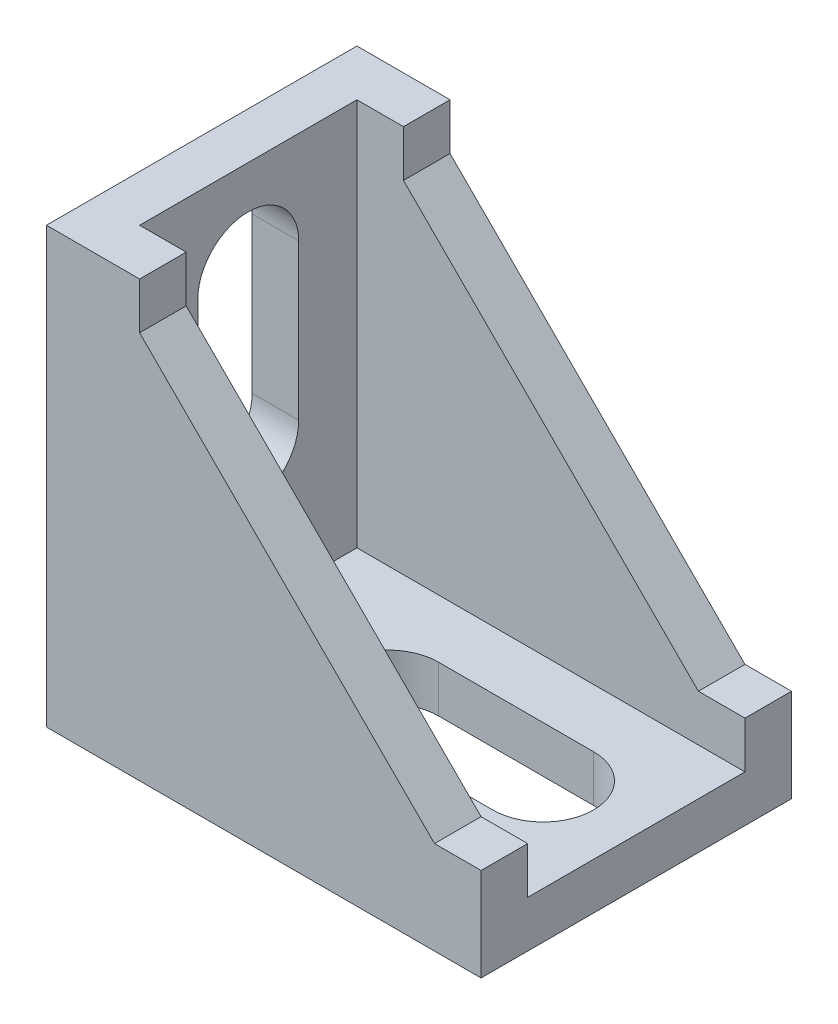
SolidWorks part; units mm, degrees
material "6063-O"
ref_plane "Front Plane" through (0, 0, 0) normal (0, 0, 1) x (1, 0, 0)
ref_plane "Top Plane" through (0, 0, 0) normal (0, 1, 0) x (1, 0, 0)
ref_plane "Right Plane" through (0, 0, 0) normal (1, 0, 0) x (0, 0, -1)
sketch "Sketch1" plane through (0, 0, 0) normal (0, 0, 1) x (1, 0, 0)
  line L1 (-14, -1.5) -> (14, -1.5)
  line L2 (-14, -1.5) -> (-14, 1.5)
  line L3 (-14, 1.5) -> (14, 1.5)
  line L4 (14, -1.5) -> (14, 1.5)
  line L5 (-14, -1.5) -> (14, 1.5) construction
  line L6 (-14, 1.5) -> (14, -1.5) construction
  line L7 (-14, 1.5) -> (-11, 1.5)
  line L8 (-14, 1.5) -> (-14, 26.5)
  line L9 (-14, 26.5) -> (-11, 26.5)
  line L10 (-11, 1.5) -> (-11, 26.5)
  point P0 (0, 0)
  dimension "D1" = 28
  dimension "D2" = 3
  dimension "D3" = 28
extrude "Boss-Extrude1" add sketch "Sketch1" along normal mid plane 20 contours L1 L4 L3 L2 | L3 L10 L9 L8
ref_plane "Plane2" through (-6.25, 6.25, 0) normal (-0.7071, 0.7071, 0) x (0, 0, 1)
sketch "Sketch3" plane through (0, 1.5, 0) normal (0, 1, 0) x (1, 0, 0)
  line L0 (14, 0) -> (-11, 0) construction
  line L1 (14, -10) -> (14, 10) construction
  line L2 (-11, -10) -> (-11, 10) construction
  line L3 (8, 0) -> (-2, 0) construction
  line L4 (8, -3.25) -> (-2, -3.25)
  line L5 (8, 3.25) -> (-2, 3.25)
  arc A0 (8, -3.25) -> (8, 3.25) centre (8, 0) ccw
  arc A1 (-2, 3.25) -> (-2, -3.25) centre (-2, 0) ccw
  point P8 (3, 0)
  dimension "D1" = 3.25
  dimension "D3" = 6
  dimension "D2" = 10
extrude "Cut-Extrude1" cut sketch "Sketch3" against normal through all
mirror "Mirror1" about plane through (-6.25, 6.25, 0) normal (-0.7071, 0.7071, 0) of "Cut-Extrude1"
sketch "Sketch4" plane through (0, 0, 10) normal (0, 0, 1) x (1, 0, 0)
  line L0 (-11, 26.5) -> (-8, 26.5)
  line L1 (-8, 26.5) -> (-8, 23.5)
  line L2 (-8, 23.5) -> (11, 4.5)
  line L3 (1.5282, 14.0282) -> (-14.0282, -1.5282) construction
  line L4 (14, 4.5) -> (11, 4.5)
  line L5 (14, 1.5) -> (14, 4.5)
  line L6 (-11, 26.5) -> (-11, 1.5)
  line L7 (-11, 1.5) -> (-11, 26.5) construction
  line L8 (-11, 1.5) -> (14, 1.5)
  point P8 (1.5, 14)
  dimension "D1" = 3
extrude "Boss-Extrude2" add sketch "Sketch4" against normal blind 3
mirror "Mirror2" about plane through (0, 0, 0) normal (0, 0, 1) of "Boss-Extrude2"
